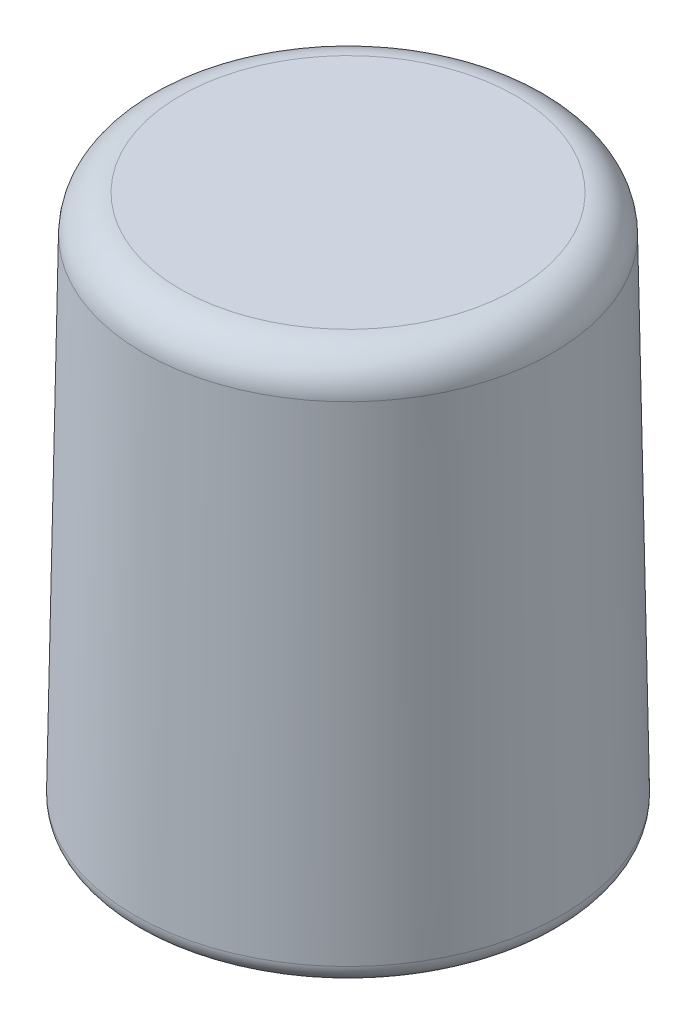
SolidWorks part; units mm, degrees
ref_plane "Front Plane" through (0, 0, 0) normal (0, 0, 1) x (1, 0, 0)
ref_plane "Top Plane" through (0, 0, 0) normal (0, 1, 0) x (1, 0, 0)
ref_plane "Right Plane" through (0, 0, 0) normal (1, 0, 0) x (0, 0, -1)
sketch "Sketch1" plane through (0, 0, 0) normal (0, 1, 0) x (1, 0, 0)
  circle A0 centre (0, 0) radius 5.75
  dimension "D1" = 11.5
extrude "Boss-Extrude1" add sketch "Sketch1" along normal blind 14.5 draft 1
fillet "Fillet1" radius 1 1 edges at (0, 14.5, 5.4969)
fillet "Fillet2" radius 0.5 1 edges at (0, 0, 5.75)
sketch "Sketch2" plane through (0, 0, 0) normal (0, -1, 0) x (1, 0, 0)
  line L0 (2.5981, -1.5) -> (-2.5981, -1.5)
  arc A0 (2.5981, -1.5) -> (-2.5981, -1.5) centre (0, 0) ccw
  dimension "D1" = 6
  dimension "D2" = 4.5
extrude "Cut-Extrude1" cut sketch "Sketch2" against normal blind 7
